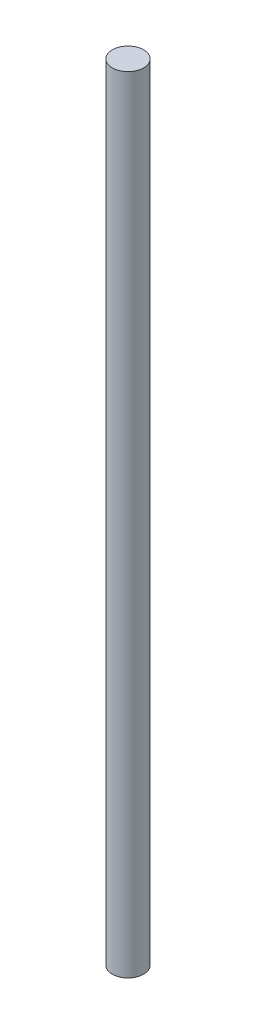
SolidWorks part; units mm, degrees
ref_plane "Front Plane" through (0, 0, 0) normal (0, 0, 1) x (1, 0, 0)
ref_plane "Top Plane" through (0, 0, 0) normal (0, 1, 0) x (1, 0, 0)
ref_plane "Right Plane" through (0, 0, 0) normal (1, 0, 0) x (0, 0, -1)
sketch "Sketch1" plane through (0, 0, 0) normal (0, 1, 0) x (1, 0, 0)
  circle A0 centre (0, 0) radius 2.5
  dimension "D1" = 5
extrude "Boss-Extrude1" add sketch "Sketch1" along normal blind 125
